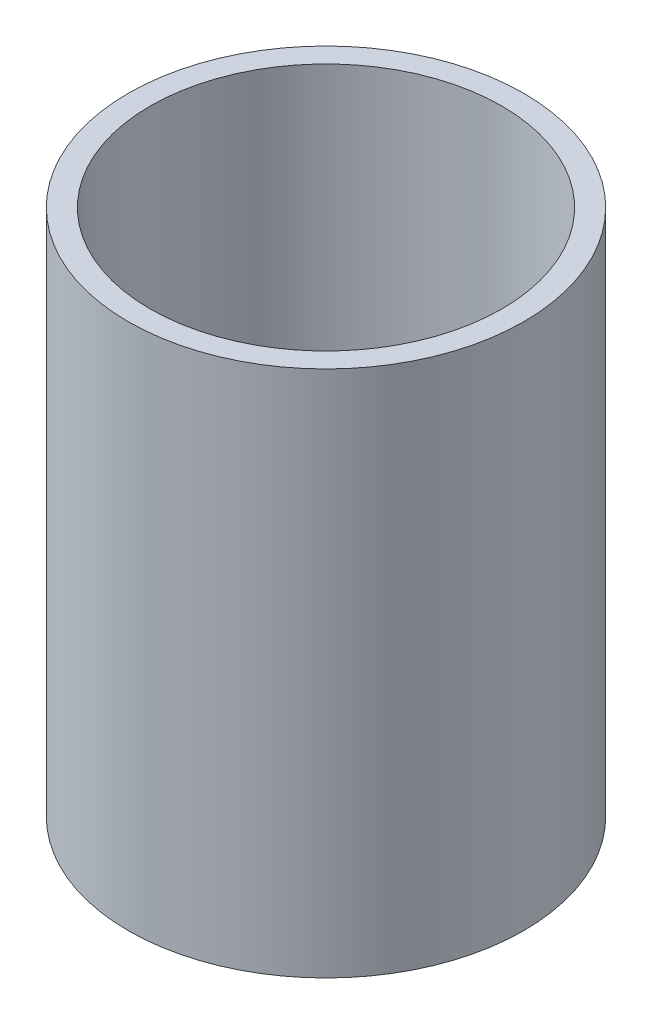
SolidWorks part; units mm, degrees
ref_plane "Front Plane" through (0, 0, 0) normal (0, 0, 1) x (1, 0, 0)
ref_plane "Top Plane" through (0, 0, 0) normal (0, 1, 0) x (1, 0, 0)
ref_plane "Right Plane" through (0, 0, 0) normal (1, 0, 0) x (0, 0, -1)
sketch "Sketch1" plane through (0, 0, 0) normal (0, 1, 0) x (1, 0, 0)
  circle A0 centre (0, 0) radius 28.575
  circle A1 centre (0, 0) radius 25.4
  dimension "D1" = 50.8
  dimension "D2" = 3.175
extrude "Boss-Extrude1" add sketch "Sketch1" along normal mid plane 76.2
ref_plane "Plane1" through (0, -8.1, 0) normal (0, -1, 0) x (-1, 0, 0)
sketch "Sketch2" plane through (0, -8.1, 0) normal (0, -1, 0) x (-1, 0, 0)
  line L0 (0, 0) -> (28.575, 0) construction
  circle A0 centre (0, 0) radius 28.575 construction
  circle A1 centre (0, 0) radius 28.575 construction
  point P3 (0, 0)
ref_plane "Plane2" through (-28.575, -8.1, 0) normal (-1, 0, 0) x (0, 0, 1)
equation "\"Container Thickness\"= 0.125in"
